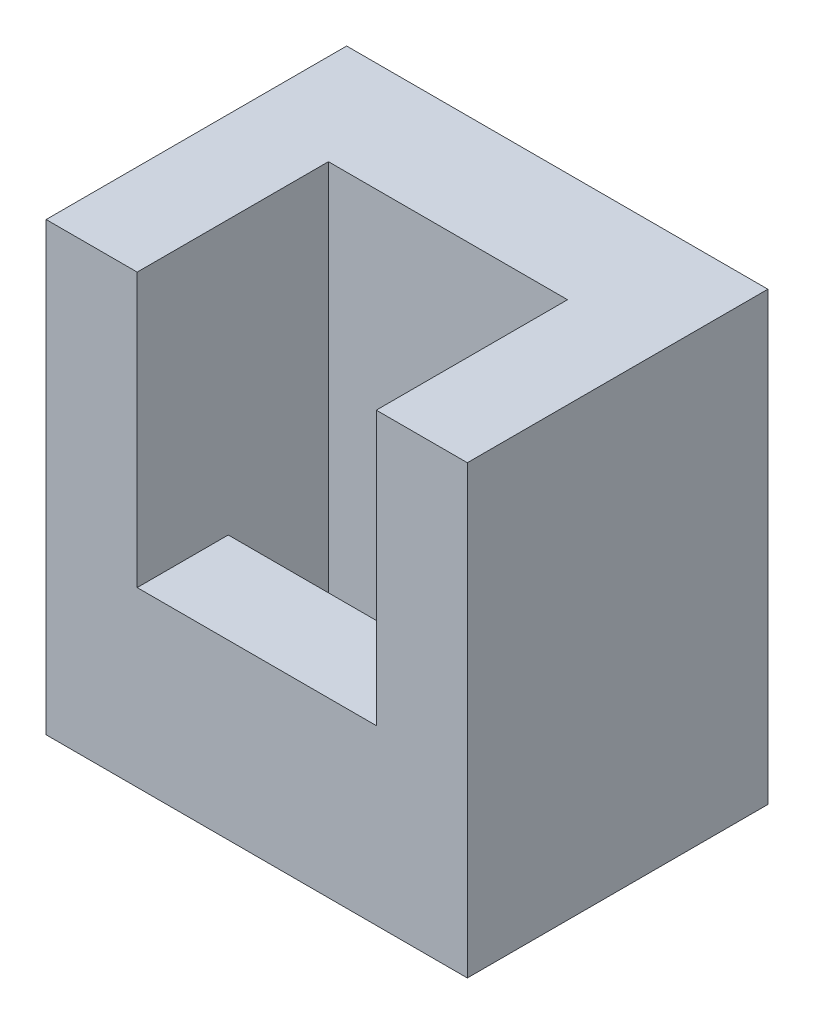
SolidWorks part; units mm, degrees
ref_plane "Front Plane" through (0, 0, 0) normal (0, 0, 1) x (1, 0, 0)
ref_plane "Top Plane" through (0, 0, 0) normal (0, 1, 0) x (1, 0, 0)
ref_plane "Right Plane" through (0, 0, 0) normal (1, 0, 0) x (0, 0, -1)
sketch "Sketch1" plane through (0, 0, 0) normal (0, 1, 0) x (1, 0, 0)
  line L1 (-13.026, 5.3523) -> (10.101, 5.3523)
  line L2 (-13.026, 5.3523) -> (-13.026, -11.1477)
  line L3 (-13.026, -11.1477) -> (10.101, -11.1477)
  line L4 (10.101, 5.3523) -> (10.101, -11.1477)
  line L5 (-8.026, -0.6477) -> (5.101, -0.6477)
  line L6 (-8.026, -0.6477) -> (-8.026, -6.1477)
  line L7 (-8.026, -6.1477) -> (5.101, -6.1477)
  line L8 (5.101, -0.6477) -> (5.101, -6.1477)
  line L9 (-2.7375, 5.3523) -> (-0.1875, 5.3523)
  line L10 (-2.7375, 5.3523) -> (-2.7375, -0.6477)
  line L11 (-2.7375, -0.6477) -> (-0.1875, -0.6477)
  line L12 (-0.1875, 5.3523) -> (-0.1875, -0.6477)
  point P12 (-1.4625, 5.3523)
  point P13 (-1.4625, -6.1477)
  point P14 (-1.4625, 5.3523)
  dimension "D1" = 2.55
  dimension "D2" = 6
  dimension "D3" = 5.5
  dimension "D4" = 13.127
  dimension "D5" = 5
  dimension "D6" = 5
extrude "Boss-Extrude1" add sketch "Sketch1" along normal blind 24.5 contours L1 L12 L5 L8 L7 L6 L10 L2 L3 L4
sketch "Sketch2" plane through (0, 0, 0) normal (0, -1, 0) x (1, 0, 0)
  line L1 (-2.7375, 0.6477) -> (-0.1875, 0.6477)
  line L2 (-2.7375, 0.6477) -> (-2.7375, -5.3523)
  line L3 (-2.7375, -5.3523) -> (-0.1875, -5.3523)
  line L4 (-0.1875, 0.6477) -> (-0.1875, -5.3523)
extrude "Cut-Extrude1" cut sketch "Sketch2" against normal blind 2
sketch "Sketch3" plane through (0, 24.5, 0) normal (0, 1, 0) x (1, 0, 0)
  line L0 (-13.026, -11.1477) -> (10.101, -11.1477) construction
  line L1 (-8.026, -6.1477) -> (5.101, -6.1477)
  line L2 (-8.026, -6.1477) -> (-8.026, -11.1477)
  line L3 (-8.026, -11.1477) -> (5.101, -11.1477)
  line L4 (5.101, -6.1477) -> (5.101, -11.1477)
  line L5 (5.101, -0.6477) -> (5.101, -6.1477) construction
extrude "Cut-Extrude2" cut sketch "Sketch3" against normal blind 15
